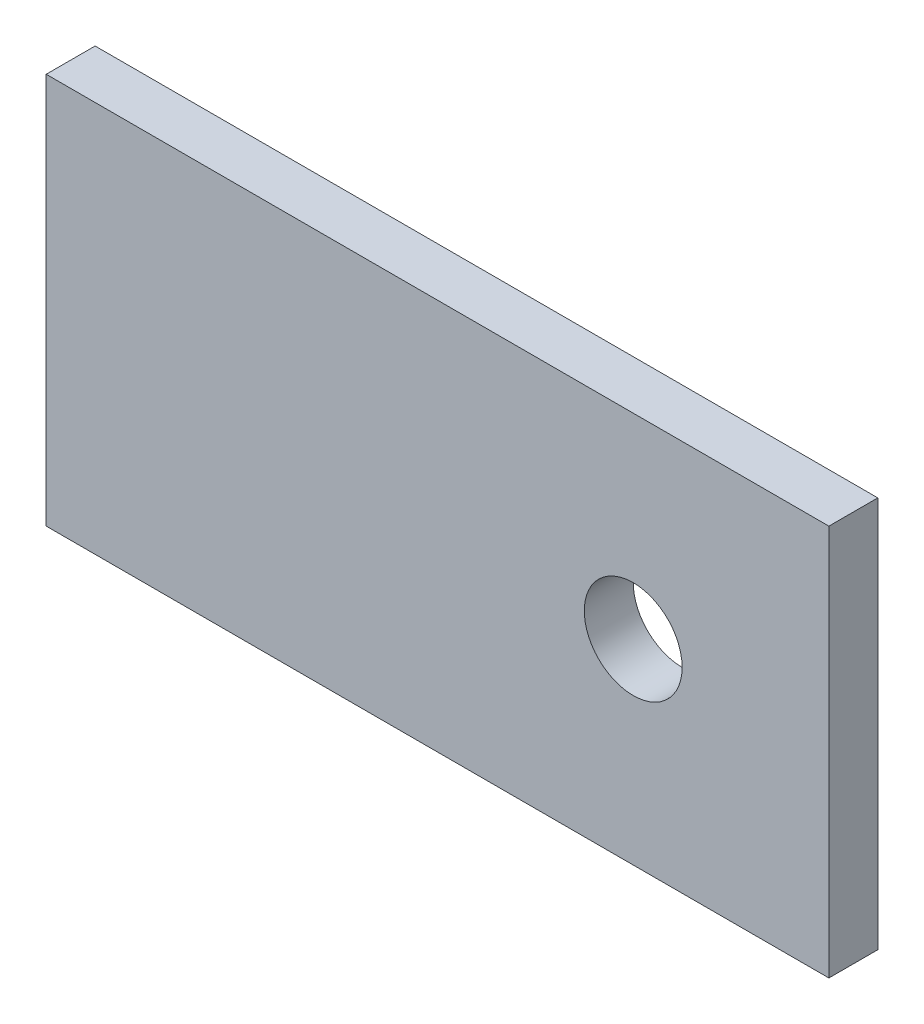
SolidWorks part; units mm, degrees
material "AISI 304"
ref_plane "Front" through (0, 0, 0) normal (0, 0, 1) x (1, 0, 0)
ref_plane "Top" through (0, 0, 0) normal (0, 1, 0) x (1, 0, 0)
ref_plane "Right" through (0, 0, 0) normal (1, 0, 0) x (0, 0, -1)
sketch "Sketch2" plane through (0, 0, 0) normal (0, 0, 1) x (1, 0, 0)
  line L1 (-38.1, 12.7) -> (12.7, 12.7)
  line L2 (-38.1, 12.7) -> (-38.1, -12.7)
  line L3 (-38.1, -12.7) -> (12.7, -12.7)
  line L4 (12.7, 12.7) -> (12.7, -12.7)
  circle A0 centre (0, 0) radius 3.175
  dimension "D1" = 6.35
  dimension "D5" = 12.7
  dimension "D2" = 50.8
  dimension "D3" = 25.4
  dimension "D4" = 12.7
extrude "Boss-Extrude1" add sketch "Sketch2" along normal blind 3.175
